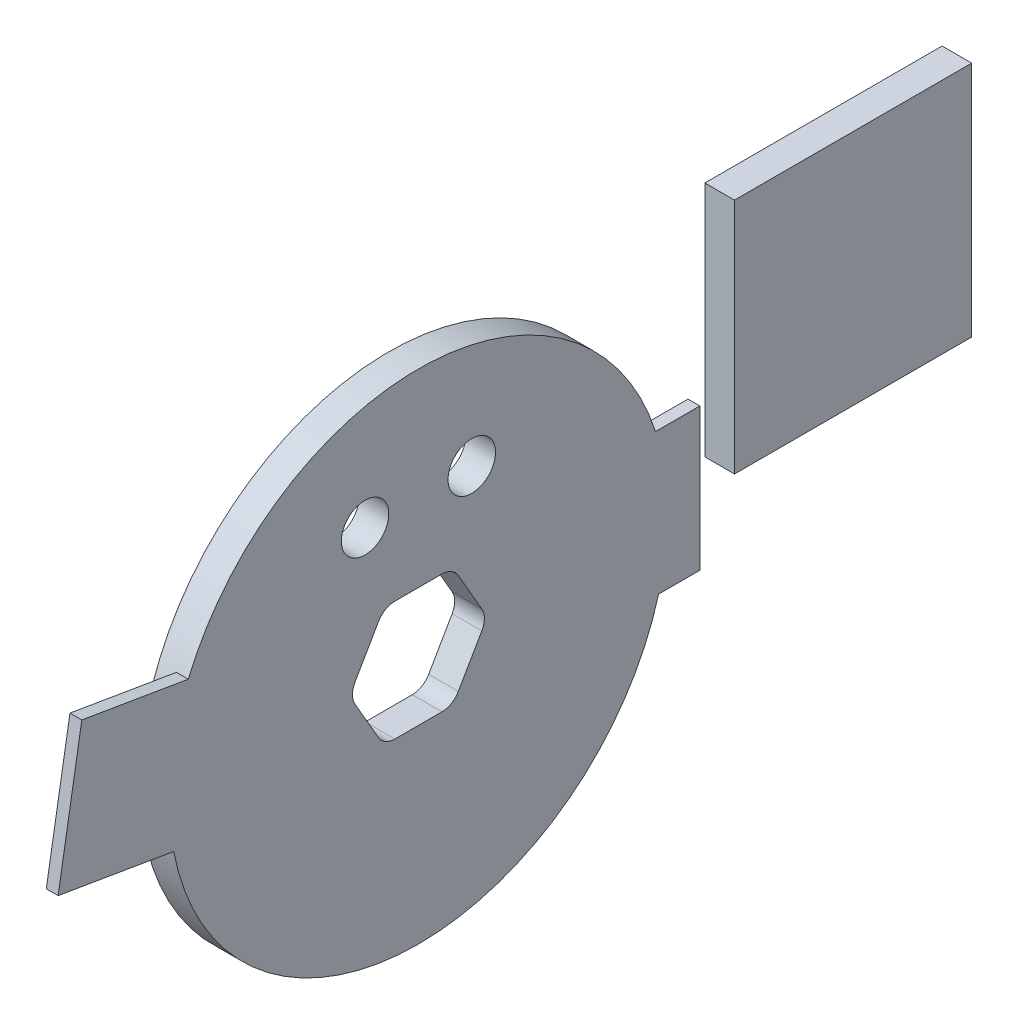
SolidWorks part; units mm, degrees
material "6061-T6 (SS)"
ref_plane "Front Plane" through (0, 0, 0) normal (0, 0, 1) x (1, 0, 0)
ref_plane "Top Plane" through (0, 0, 0) normal (0, 1, 0) x (1, 0, 0)
ref_plane "Right Plane" through (0, 0, 0) normal (1, 0, 0) x (0, 0, -1)
sketch "Sketch1" plane through (0, 0, 0) normal (1, 0, 0) x (0, 0, -1)
  line L7 (3.6882, 6.3881) -> (-3.6882, 6.3881)
  line L8 (-3.6882, 6.3881) -> (-7.3763, 0)
  line L9 (-7.3763, 0) -> (-3.6882, -6.3881)
  line L10 (-3.6882, -6.3881) -> (3.6882, -6.3881)
  line L11 (3.6882, -6.3881) -> (7.3763, 0)
  line L12 (7.3763, 0) -> (3.6882, 6.3881)
  circle A0 centre (0, 0) radius 29.21
  circle A1 centre (0, 0) radius 6.3881 construction
  dimension "D1" = 58.42
  dimension "D2" = 12.7762
extrude "Boss-Extrude1" add sketch "Sketch1" along normal blind 3.175
fillet "Fillet1" radius 2.032 6 edges at (1.5875, 6.3881, 3.6882) (1.5875, 0, 7.3763) (1.5875, -6.3881, 3.6882) (1.5875, -6.3881, -3.6882) (1.5875, 0, -7.3763) (1.5875, 6.3881, -3.6882)
sketch "Sketch3" plane through (0, 0, 0) normal (-1, 0, 0) x (0, 0, 1)
  line L0 (0, 0) -> (0, 28.3202) construction
  line L1 (5.715, 14.8106) -> (-5.715, 14.8106) construction
  circle A0 centre (-5.715, 14.8106) radius 2.54
  circle A1 centre (5.715, 14.8106) radius 2.54
  circle A2 centre (0, 0) radius 13.335 construction
  point P7 (0, 14.8106)
  dimension "D1" = 11.43
  dimension "D2" = 5.08
  dimension "D3" = 26.67
extrude "Cut-Extrude2" cut sketch "Sketch3" against normal through all
sketch "Sketch4" plane through (0, 0, 0) normal (-1, 0, 0) x (0, 0, 1)
  circle A0 centre (0, 0) radius 26.67
  circle A1 centre (0, 0) radius 29.21 construction
  dimension "D1" = 2.54
extrude "Cut-Extrude3" cut sketch "Sketch4" against normal through all flip side to cut
sketch "Sketch5" [suppressed] plane through (3.175, 0, 0) normal (1, 0, 0) x (0, 0, -1)
  line L1 (61.7527, 50.2411) -> (36.3527, 50.2411)
  line L2 (61.7527, 50.2411) -> (61.7527, 24.8411)
  line L3 (61.7527, 24.8411) -> (36.3527, 24.8411)
  line L4 (36.3527, 50.2411) -> (36.3527, 24.8411)
  line L5 (61.7527, 50.2411) -> (36.3527, 24.8411) construction
  line L6 (61.7527, 24.8411) -> (36.3527, 50.2411) construction
  point P4 (49.0527, 37.5411)
  dimension "D1" = 25.4
extrude "Boss-Extrude2" [suppressed] add sketch "Sketch5" against normal up to surface (3.175 mm away) separate body
sketch "Sketch6" [suppressed] plane through (3.175, 0, 0) normal (1, 0, 0) x (0, 0, -1)
  line L0 (11.8049, 22.9674) -> (21.5814, 11.2765)
  line L1 (11.8049, 22.9674) -> (25.6384, 34.5357)
  line L2 (21.5814, 11.2765) -> (35.4149, 22.8448)
  line L3 (25.6384, 34.5357) -> (35.4149, 22.8448)
  line L4 (-12.7092, -12.0015) -> (-2.9327, -23.6924)
  line L5 (-12.7092, -12.0015) -> (-28.2608, -25.0066)
  line L6 (-2.9327, -23.6924) -> (-18.4843, -36.6975)
  line L7 (-28.2608, -25.0066) -> (-18.4843, -36.6975)
  dimension "D1" = 15.24
extrude "Boss-Extrude3" [suppressed] add sketch "Sketch6" against normal blind 1.27
sketch "Sketch7" plane through (3.175, 0, 0) normal (1, 0, 0) x (0, 0, -1)
  line L0 (33.8423, 0) -> (59.2423, 0)
  line L1 (33.8423, 0) -> (33.8423, 25.4)
  line L2 (59.2423, 0) -> (59.2423, 25.4)
  line L3 (33.8423, 25.4) -> (59.2423, 25.4)
  dimension "D1" = 25.4
extrude "Boss-Extrude4" add sketch "Sketch7" against normal up to surface (3.175 mm away) separate body up to face at (0, 0, 0)
sketch "Sketch8" plane through (3.175, 0, 0) normal (1, 0, 0) x (0, 0, -1)
  line L0 (-20.187, 9.4647) -> (-22.7211, -5.5632)
  line L1 (-20.187, 9.4647) -> (-36.0381, 12.1375)
  line L2 (-22.7211, -5.5632) -> (-38.5722, -2.8903)
  line L3 (-36.0381, 12.1375) -> (-38.5722, -2.8903)
  line L4 (19.301, 8.167) -> (19.301, -7.073)
  line L5 (19.301, 8.167) -> (30.1332, 8.167)
  line L6 (19.301, -7.073) -> (30.1332, -7.073)
  line L7 (30.1332, 8.167) -> (30.1332, -7.073)
  dimension "D1" = 15.24
extrude "Boss-Extrude5" add sketch "Sketch8" against normal blind 1.27
